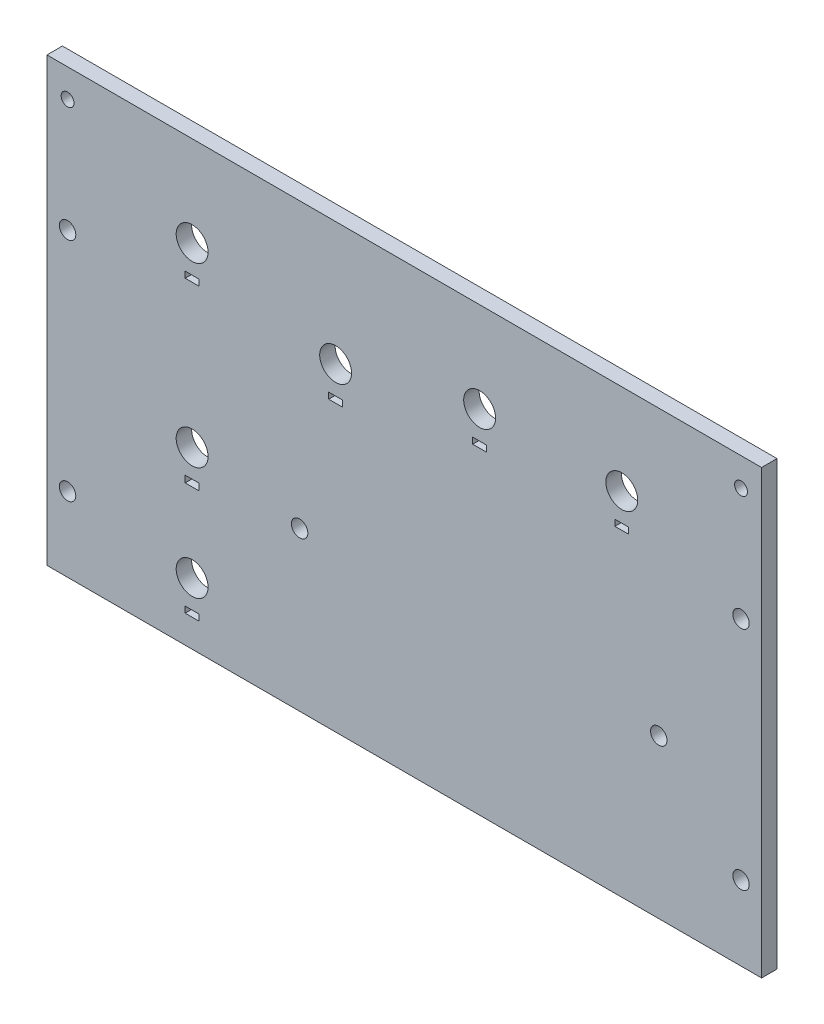
SolidWorks part; units mm, degrees
ref_plane "Front Plane" through (0, 0, 0) normal (0, 0, 1) x (1, 0, 0)
ref_plane "Top Plane" through (0, 0, 0) normal (0, 1, 0) x (1, 0, 0)
ref_plane "Right Plane" through (0, 0, 0) normal (1, 0, 0) x (0, 0, -1)
sketch "Sketch1" plane through (0, 0, 0) normal (0, 0, 1) x (1, 0, 0)
  line L0 (0, 43) -> (139, 43) construction
  line L1 (0, 0) -> (139, 0)
  line L2 (0, 0) -> (0, 86)
  line L3 (0, 86) -> (139, 86)
  line L4 (139, 0) -> (139, 86)
  line L5 (69.5, 86) -> (69.5, 0) construction
  line L17 (28.228, 11.9945) -> (28.228, 5.9945) construction
  line L30 (26.878, 5.3945) -> (29.578, 5.3945)
  line L31 (26.878, 5.3945) -> (26.878, 6.5945)
  line L43 (26.878, 6.5945) -> (29.578, 6.5945)
  line L44 (29.578, 5.3945) -> (29.578, 6.5945)
  line L45 (26.878, 5.3945) -> (29.578, 6.5945) construction
  line L50 (26.878, 6.5945) -> (29.578, 5.3945) construction
  line L51 (111.8065, 68.4195) -> (111.8065, 62.4195) construction
  line L52 (84.1546, 68.4195) -> (84.1546, 62.4195) construction
  line L57 (82.8046, 61.8195) -> (85.5046, 61.8195)
  line L58 (82.8046, 61.8195) -> (82.8046, 63.0195)
  line L59 (82.8046, 63.0195) -> (85.5046, 63.0195)
  line L64 (85.5046, 61.8195) -> (85.5046, 63.0195)
  line L65 (82.8046, 61.8195) -> (85.5046, 63.0195) construction
  line L66 (56.1418, 62) -> (56.1418, 56) construction
  line L67 (54.7918, 55.4) -> (57.4918, 55.4)
  line L68 (54.7918, 55.4) -> (54.7918, 56.6)
  line L69 (54.7918, 56.6) -> (57.4918, 56.6)
  line L70 (57.4918, 55.4) -> (57.4918, 56.6)
  line L71 (54.7918, 55.4) -> (57.4918, 56.6) construction
  line L72 (54.7918, 56.6) -> (57.4918, 55.4) construction
  line L80 (82.8046, 63.0195) -> (85.5046, 61.8195) construction
  line L81 (28.228, 68.4195) -> (28.228, 62.4195) construction
  line L82 (110.4565, 61.8195) -> (113.1565, 61.8195)
  line L83 (110.4565, 61.8195) -> (110.4565, 63.0195)
  line L84 (110.4565, 63.0195) -> (113.1565, 63.0195)
  line L85 (113.1565, 61.8195) -> (113.1565, 63.0195)
  line L86 (110.4565, 61.8195) -> (113.1565, 63.0195) construction
  line L87 (110.4565, 63.0195) -> (113.1565, 61.8195) construction
  line L88 (26.878, 61.8195) -> (29.578, 61.8195)
  line L89 (26.878, 61.8195) -> (26.878, 63.0195)
  line L90 (26.878, 63.0195) -> (29.578, 63.0195)
  line L91 (29.578, 61.8195) -> (29.578, 63.0195)
  line L92 (26.878, 61.8195) -> (29.578, 63.0195) construction
  line L93 (26.878, 63.0195) -> (29.578, 61.8195) construction
  line L94 (28.228, 33.9945) -> (28.228, 27.9945) construction
  line L95 (26.878, 27.3398) -> (29.578, 27.3398)
  line L96 (26.878, 27.3398) -> (26.878, 28.6493)
  line L97 (26.878, 28.6493) -> (29.578, 28.6493)
  line L98 (29.578, 27.3398) -> (29.578, 28.6493)
  line L99 (26.878, 27.3398) -> (29.578, 28.6493) construction
  line L100 (26.878, 28.6493) -> (29.578, 27.3398) construction
  circle A4 centre (4, 58.5) radius 1.6
  circle A5 centre (135, 58.5) radius 1.6
  circle A6 centre (135, 14.5) radius 1.6
  circle A7 centre (4, 14.5) radius 1.6
  circle A9 centre (49.1366, 30.8058) radius 1.6
  circle A11 centre (119, 30.8058) radius 1.6
  circle A19 centre (56.1418, 62) radius 3.1
  circle A21 centre (28.228, 11.9945) radius 3.1
  circle A22 centre (111.8065, 68.4195) radius 3.1
  circle A24 centre (84.1546, 68.4195) radius 3.1
  circle A27 centre (135, 80.5) radius 1.25
  circle A28 centre (4, 80.5) radius 1.25
  circle A29 centre (28.228, 68.4195) radius 3.1
  circle A30 centre (28.228, 33.9945) radius 3.1
  point P9 (28.228, 62.4195)
  point P28 (28.228, 27.9945)
  point P32 (84.1546, 62.4195)
  point P39 (28.228, 5.9945)
  point P47 (111.8065, 62.4195)
  point P65 (0, 0)
  point P66 (0, 0)
  point P67 (56.1418, 66.07)
  point P68 (84.1546, 70.9487)
  point P69 (0, 0)
  point P70 (56.1418, 36.115)
  point P71 (30.2271, 36.6741)
  point P72 (0, 0)
  point P73 (0, 0)
  point P74 (0, 0)
  point P75 (0, 0)
  point P76 (0, 0)
  point P77 (0, 0)
  point P78 (28.228, 11.9945)
  point P116 (56.1418, 56)
  dimension "D8" = 3.2
  dimension "D19" = 3.2
  dimension "D27" = 2.5
  dimension "D17" = 6.2
  dimension "D1" = 139
  dimension "D2" = 86
  dimension "D13" = 27.5
  dimension "D11" = 131
  dimension "D12" = 4
  dimension "D20" = 4
  dimension "D18" = 20
  dimension "D3" = 14.5
  dimension "D50" = 1.2
  dimension "D51" = 6
  dimension "D24" = 6
  dimension "D26" = 6
  dimension "D22" = 6
  dimension "D14" = 44
  dimension "D28" = 5.5
  dimension "D29" = 4
  dimension "D30" = 4
  dimension "D32" = 2.7
  dimension "D4" = 6
  dimension "D6" = 6
  dimension "D7" = 24
  dimension "D15" = 22
  dimension "D9" = 2
  dimension "D10" = 2
extrude "Boss-Extrude1" add sketch "Sketch1" along normal blind 3
equation "\"D13@Sketch1\"=22+5.5"
